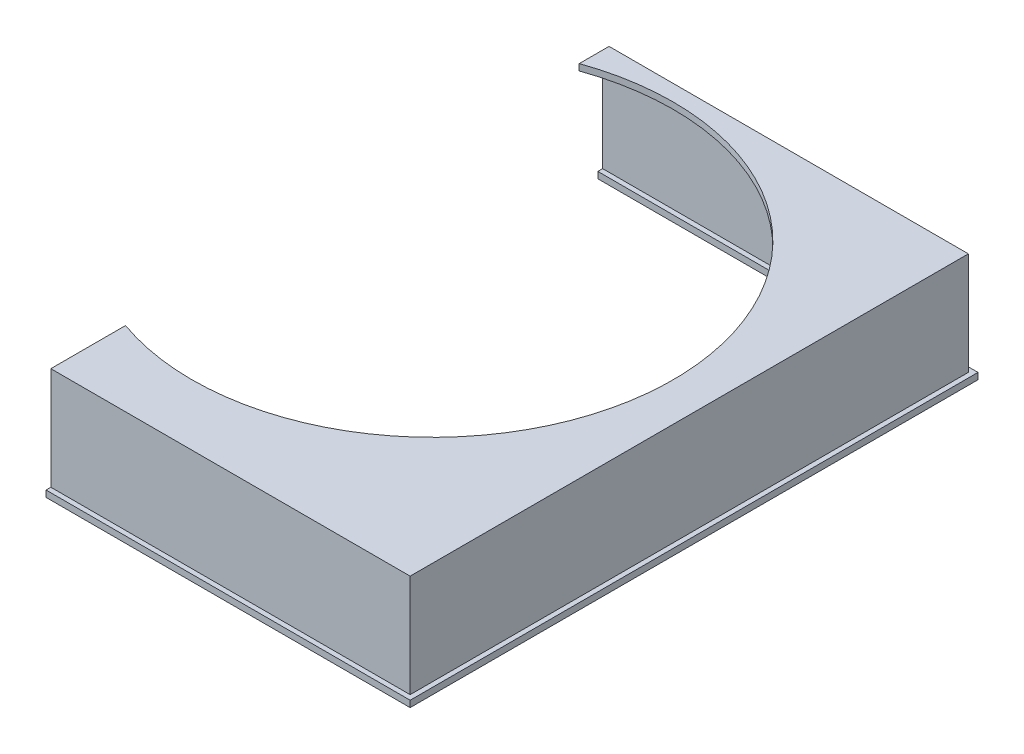
SolidWorks part; units mm, degrees
ref_plane "前视基准面" through (0, 0, 0) normal (0, 0, 1) x (1, 0, 0)
ref_plane "上视基准面" through (0, 0, 0) normal (0, 1, 0) x (1, 0, 0)
ref_plane "右视基准面" through (0, 0, 0) normal (1, 0, 0) x (0, 0, -1)
other "Configuration Table"
sketch "草图1" plane through (0, 0, 0) normal (0, 1, 0) x (1, 0, 0)
  line L1 (0, 0) -> (220, 0)
  line L2 (0, 0) -> (0, -170)
  line L3 (0, -170) -> (220, -170)
  line L4 (220, 0) -> (220, -170)
  line L9 (-2, 2) -> (222, 2)
  line L10 (-2, 2) -> (-2, -172)
  line L11 (-2, -172) -> (222, -172)
  line L12 (222, 2) -> (222, -172)
  point P4 (-2, 0)
  point P5 (0, 2)
  point P7 (222, -170)
  point P8 (220, -172)
  dimension "D1" = 220
  dimension "D2" = 170
  dimension "D3" = 2
  dimension "D4" = 2
  dimension "D5" = 2
  dimension "D6" = 2
extrude "凸台-拉伸1" add sketch "草图1" along normal blind 32
sketch "草图2" plane through (0, 0, 0) normal (0, 1, 0) x (1, 0, 0)
  line L0 (220, -170) -> (220, 0) construction
  line L1 (0, -170) -> (220, -170) construction
  line L2 (0, 0) -> (0, -170) construction
  line L3 (220, 0) -> (0, 0) construction
  line L14 (-3.5, 3.5) -> (223.5, 3.5)
  line L15 (-3.5, 3.5) -> (-3.5, -173.5)
  line L16 (-3.5, -173.5) -> (223.5, -173.5)
  line L17 (223.5, 3.5) -> (223.5, -173.5)
  line L18 (218.5, -168.5) -> (1.5, -168.5)
  line L19 (218.5, -168.5) -> (218.5, -1.5)
  line L20 (218.5, -1.5) -> (1.5, -1.5)
  line L21 (1.5, -168.5) -> (1.5, -1.5)
  point P0 (-3.5, 2)
  point P1 (-2, 3.5)
  point P2 (222, -173.5)
  point P3 (223.5, -172)
  point P4 (220, -168.5)
  point P5 (218.5, -170)
  point P8 (0, -1.5)
  point P11 (1.5, 0)
  point P14 (0, 0)
  point P17 (220, -170)
  point P18 (-2, 2)
  point P19 (222, -172)
  dimension "D1" = 1.5
  dimension "D2" = 1.5
  dimension "D3" = 1.5
  dimension "D4" = 1.5
  dimension "D5" = 1.5
  dimension "D6" = 1.5
  dimension "D7" = 1.5
  dimension "D8" = 1.5
extrude "凸台-拉伸2" add sketch "草图2" against normal blind 2
ref_plane "基准面1" through (0, 32, 0) normal (0, 1, 0) x (1, 0, 0)
sketch "草图3" plane through (0, 32, 0) normal (0, 1, 0) x (1, 0, 0)
  line L0 (-2, 2) -> (-2, -172) construction
  line L1 (222, -172) -> (222, 2) construction
  line L7 (-2, 2) -> (220, 2)
  line L8 (-2, 2) -> (-2, -170)
  line L9 (-2, -170) -> (220, -170)
  line L10 (220, 2) -> (220, -170)
  circle A0 centre (135, -78) radius 75
  point P0 (-2, -78)
  point P1 (222, -78)
  point P5 (210, -78)
  point P8 (60, -78)
  point P9 (135, -78)
  dimension "D1" = 80
  dimension "D2" = 12
  dimension "D3" = 62
  dimension "D4" = 75
extrude "凸台-拉伸3" add sketch "草图3" against normal blind 2
sketch "草图4" plane through (0, 32, 0) normal (0, 1, 0) x (1, 0, 0)
  line L0 (223.5, 3.5) -> (-3.5, 3.5) construction
  line L1 (-3.5, -173.5) -> (223.5, -173.5) construction
  line L2 (-3.5, 3.5) -> (110, 3.5)
  line L3 (-3.5, 3.5) -> (-3.5, -173.5)
  line L4 (-3.5, -173.5) -> (110, -173.5)
  line L5 (110, 3.5) -> (110, -173.5)
  point P0 (110, 3.5)
extrude "切除-拉伸1" cut sketch "草图4" against normal through all
